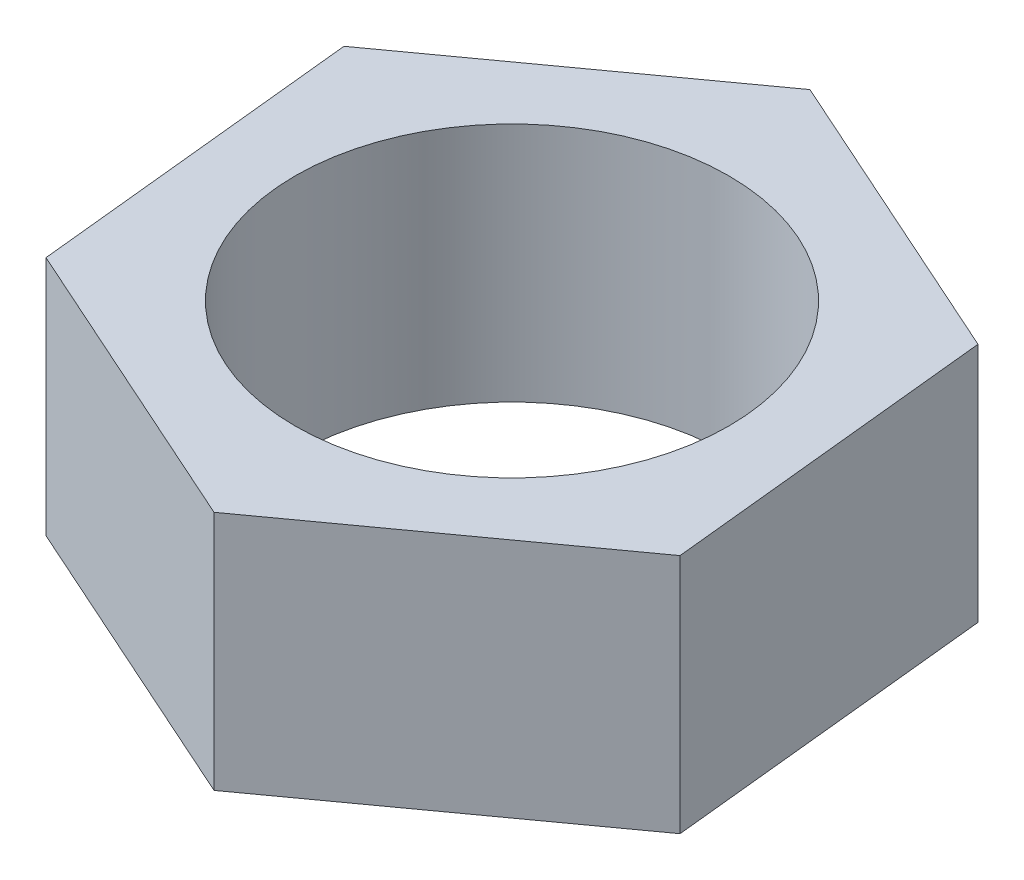
SolidWorks part; units mm, degrees
ref_plane "Front Plane" through (0, 0, 0) normal (0, 0, 1) x (1, 0, 0)
ref_plane "Top Plane" through (0, 0, 0) normal (0, 1, 0) x (1, 0, 0)
ref_plane "Right Plane" through (0, 0, 0) normal (1, 0, 0) x (0, 0, -1)
sketch "Sketch1" plane through (0, 0, 0) normal (0, 1, 0) x (1, 0, 0)
  line L1 (11.2305, 8.1164) -> (-1.4137, 13.7841)
  line L2 (-1.4137, 13.7841) -> (-12.6442, 5.6677)
  line L3 (-12.6442, 5.6677) -> (-11.2305, -8.1164)
  line L4 (-11.2305, -8.1164) -> (1.4137, -13.7841)
  line L5 (1.4137, -13.7841) -> (12.6442, -5.6677)
  line L6 (12.6442, -5.6677) -> (11.2305, 8.1164)
  circle A0 centre (0, 0) radius 12 construction
  circle A1 centre (0, 0) radius 9
  dimension "D1" = 24
  dimension "D2" = 18
extrude "Boss-Extrude1" add sketch "Sketch1" along normal blind 10
